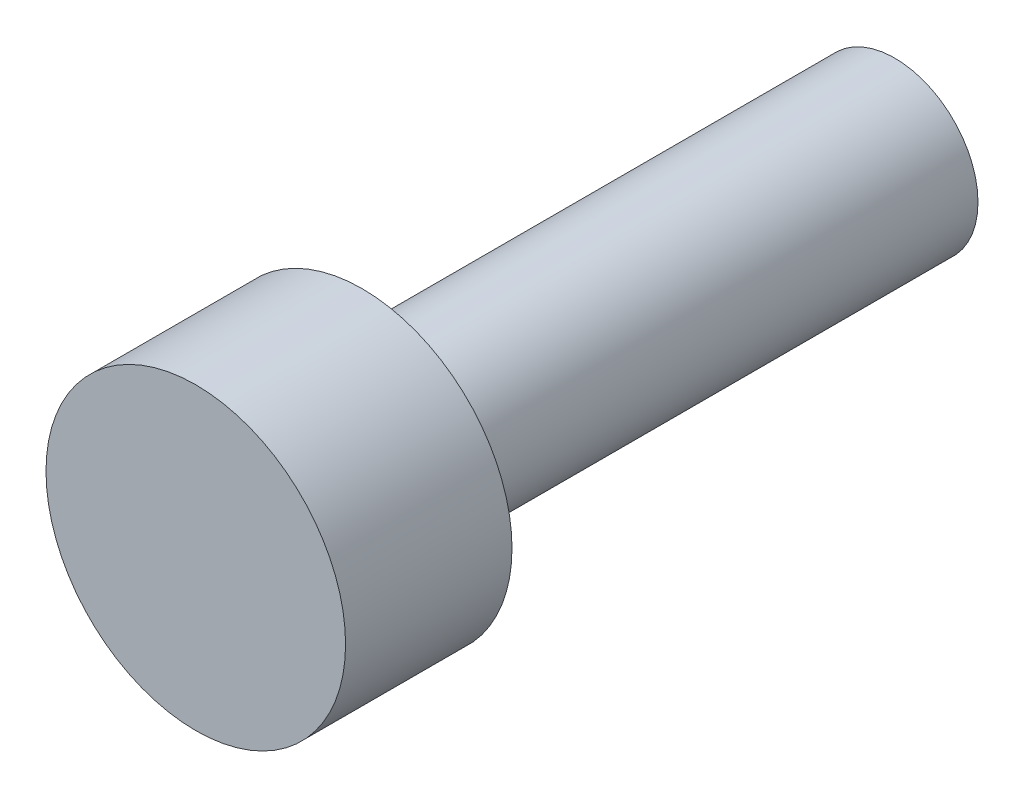
SolidWorks part; units mm, degrees
ref_plane "Front Plane" through (0, 0, 0) normal (0, 0, 1) x (1, 0, 0)
ref_plane "Top Plane" through (0, 0, 0) normal (0, 1, 0) x (1, 0, 0)
ref_plane "Right Plane" through (0, 0, 0) normal (1, 0, 0) x (0, 0, -1)
sketch "Sketch1" plane through (0, 0, 0) normal (0, 0, 1) x (1, 0, 0)
  circle A0 centre (0, 0) radius 2.5
  dimension "D1" = 5
extrude "Boss-Extrude1" add sketch "Sketch1" along normal blind 16
sketch "Sketch2" plane through (0, 0, 16) normal (0, 0, 1) x (1, 0, 0)
  circle A0 centre (0, 0) radius 4.5
  dimension "D1" = 9
extrude "Boss-Extrude2" add sketch "Sketch2" along normal blind 5
